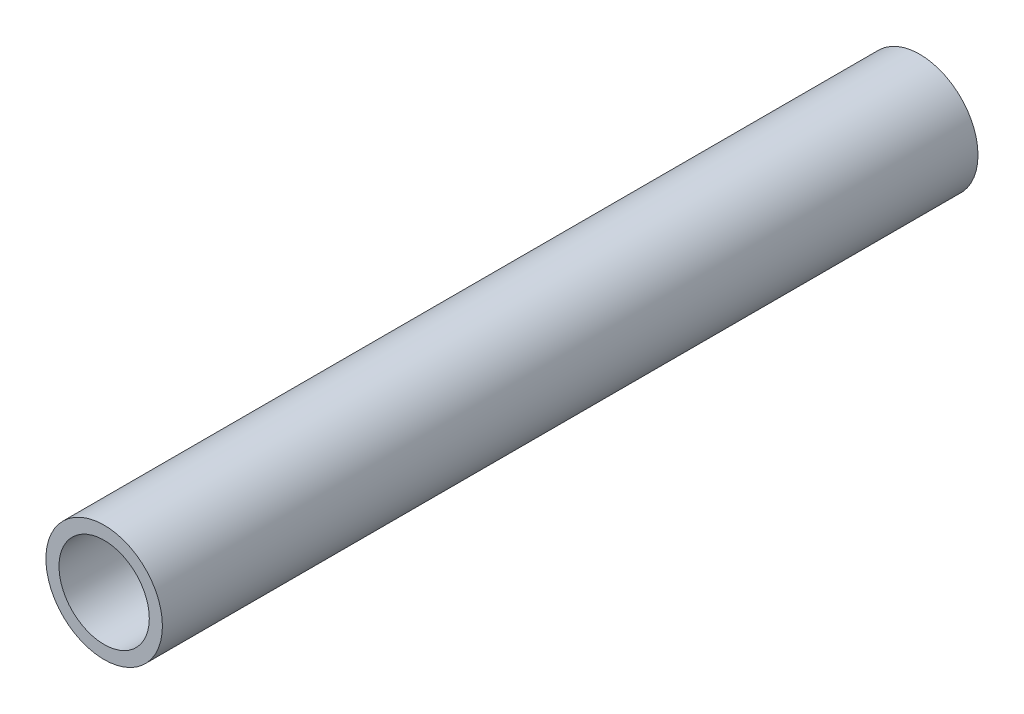
SolidWorks part; units mm, degrees
ref_plane "Спереди" through (0, 0, 0) normal (0, 0, 1) x (1, 0, 0)
ref_plane "Сверху" through (0, 0, 0) normal (0, 1, 0) x (1, 0, 0)
ref_plane "Справа" through (0, 0, 0) normal (1, 0, 0) x (0, 0, -1)
sketch "Эскиз1" plane through (0, 0, 0) normal (0, 0, 1) x (1, 0, 0)
  circle A0 centre (0, 0) radius 1
  circle A1 centre (0, 0) radius 0.775
extrude "Бобышка-Вытянуть1" add sketch "Эскиз1" along normal blind 14
